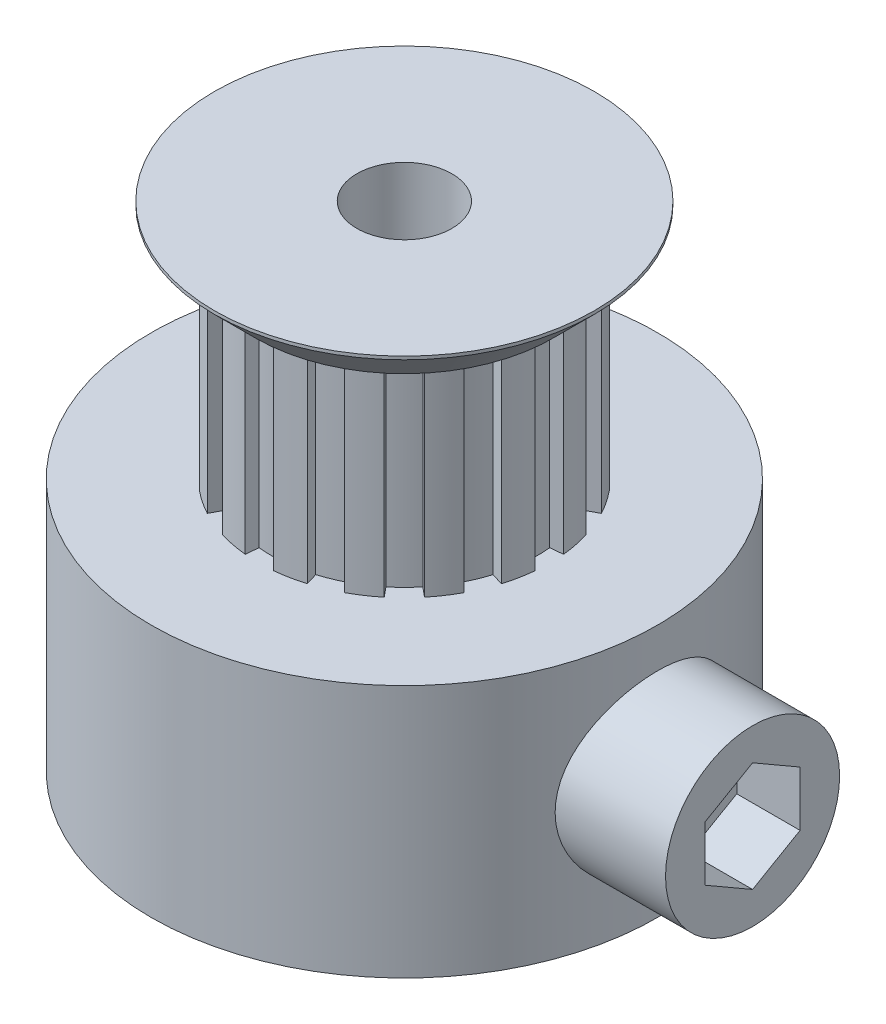
SolidWorks part; units mm, degrees
ref_plane "Front Plane" through (0, 0, 0) normal (0, 0, 1) x (1, 0, 0)
ref_plane "Top Plane" through (0, 0, 0) normal (0, 1, 0) x (1, 0, 0)
ref_plane "Right Plane" through (0, 0, 0) normal (1, 0, 0) x (0, 0, -1)
sketch "Sketch1" plane through (0, 0, 0) normal (0, 1, 0) x (1, 0, 0)
  circle A0 centre (0, 0) radius 8
  dimension "D1" = 16
extrude "Boss-Extrude1" add sketch "Sketch1" along normal blind 8
sketch "Sketch2" plane through (0, 8, 0) normal (0, 1, 0) x (1, 0, 0)
  circle A0 centre (0, 0) radius 4.6
  dimension "D1" = 9.2
extrude "Boss-Extrude2" add sketch "Sketch2" along normal blind 6.2
sketch "Sketch6" plane through (0, 14.2, 0) normal (0, 1, 0) x (1, 0, 0)
  line L0 (0, 0) -> (0, 4.6) construction
  line L1 (-0.4509, 4.5778) -> (0, 0) construction
  line L2 (0.4509, 4.5778) -> (0, 0) construction
  line L3 (-0.4509, 4.5778) -> (-0.4117, 4.1798)
  line L4 (0.4509, 4.5778) -> (0.4117, 4.1798)
  line L5 (2.1684, 4.0568) -> (1.9799, 3.7041)
  line L6 (1.3353, 4.4019) -> (1.2192, 4.0191)
  line L7 (3.5558, 2.9182) -> (3.2466, 2.6645)
  line L8 (2.9182, 3.5558) -> (2.6645, 3.2466)
  line L9 (4.4019, 1.3353) -> (4.0191, 1.2192)
  line L10 (4.0568, 2.1684) -> (3.7041, 1.9799)
  line L11 (4.5778, -0.4509) -> (4.1798, -0.4117)
  line L12 (4.5778, 0.4509) -> (4.1798, 0.4117)
  line L13 (4.0568, -2.1684) -> (3.7041, -1.9799)
  line L14 (4.4019, -1.3353) -> (4.0191, -1.2192)
  line L15 (2.9182, -3.5558) -> (2.6645, -3.2466)
  line L16 (3.5558, -2.9182) -> (3.2466, -2.6645)
  line L17 (1.3353, -4.4019) -> (1.2192, -4.0191)
  line L18 (2.1684, -4.0568) -> (1.9799, -3.7041)
  line L19 (-0.4509, -4.5778) -> (-0.4117, -4.1798)
  line L20 (0.4509, -4.5778) -> (0.4117, -4.1798)
  line L21 (-2.1684, -4.0568) -> (-1.9799, -3.7041)
  line L22 (-1.3353, -4.4019) -> (-1.2192, -4.0191)
  line L23 (-3.5558, -2.9182) -> (-3.2466, -2.6645)
  line L24 (-2.9182, -3.5558) -> (-2.6645, -3.2466)
  line L25 (-4.4019, -1.3353) -> (-4.0191, -1.2192)
  line L26 (-4.0568, -2.1684) -> (-3.7041, -1.9799)
  line L27 (-4.5778, 0.4509) -> (-4.1798, 0.4117)
  line L28 (-4.5778, -0.4509) -> (-4.1798, -0.4117)
  line L29 (-4.0568, 2.1684) -> (-3.7041, 1.9799)
  line L30 (-4.4019, 1.3353) -> (-4.0191, 1.2192)
  line L31 (-2.9182, 3.5558) -> (-2.6645, 3.2466)
  line L32 (-3.5558, 2.9182) -> (-3.2466, 2.6645)
  line L33 (-1.3353, 4.4019) -> (-1.2192, 4.0191)
  line L34 (-2.1684, 4.0568) -> (-1.9799, 3.7041)
  circle A0 centre (0, 0) radius 4.6 construction
  circle A1 centre (0, 0) radius 4.6 construction
  arc A2 (-0.4509, 4.5778) -> (0.4509, 4.5778) centre (0, 0) cw
  circle A3 centre (0, 0) radius 4.6 construction
  arc A4 (-0.4117, 4.1798) -> (0.4117, 4.1798) centre (0, 0) cw
  arc A5 (1.2192, 4.0191) -> (1.9799, 3.7041) centre (0, 0) cw
  arc A6 (1.3353, 4.4019) -> (2.1684, 4.0568) centre (0, 0) cw
  arc A7 (2.6645, 3.2466) -> (3.2466, 2.6645) centre (0, 0) cw
  arc A8 (2.9182, 3.5558) -> (3.5558, 2.9182) centre (0, 0) cw
  arc A9 (3.7041, 1.9799) -> (4.0191, 1.2192) centre (0, 0) cw
  arc A10 (4.0568, 2.1684) -> (4.4019, 1.3353) centre (0, 0) cw
  arc A11 (4.1798, 0.4117) -> (4.1798, -0.4117) centre (0, 0) cw
  arc A12 (4.5778, 0.4509) -> (4.5778, -0.4509) centre (0, 0) cw
  arc A13 (4.0191, -1.2192) -> (3.7041, -1.9799) centre (0, 0) cw
  arc A14 (4.4019, -1.3353) -> (4.0568, -2.1684) centre (0, 0) cw
  arc A15 (3.2466, -2.6645) -> (2.6645, -3.2466) centre (0, 0) cw
  arc A16 (3.5558, -2.9182) -> (2.9182, -3.5558) centre (0, 0) cw
  arc A17 (1.9799, -3.7041) -> (1.2192, -4.0191) centre (0, 0) cw
  arc A18 (2.1684, -4.0568) -> (1.3353, -4.4019) centre (0, 0) cw
  arc A19 (0.4117, -4.1798) -> (-0.4117, -4.1798) centre (0, 0) cw
  arc A20 (0.4509, -4.5778) -> (-0.4509, -4.5778) centre (0, 0) cw
  arc A21 (-1.2192, -4.0191) -> (-1.9799, -3.7041) centre (0, 0) cw
  arc A22 (-1.3353, -4.4019) -> (-2.1684, -4.0568) centre (0, 0) cw
  arc A23 (-2.6645, -3.2466) -> (-3.2466, -2.6645) centre (0, 0) cw
  arc A24 (-2.9182, -3.5558) -> (-3.5558, -2.9182) centre (0, 0) cw
  arc A25 (-3.7041, -1.9799) -> (-4.0191, -1.2192) centre (0, 0) cw
  arc A26 (-4.0568, -2.1684) -> (-4.4019, -1.3353) centre (0, 0) cw
  arc A27 (-4.1798, -0.4117) -> (-4.1798, 0.4117) centre (0, 0) cw
  arc A28 (-4.5778, -0.4509) -> (-4.5778, 0.4509) centre (0, 0) cw
  arc A29 (-4.0191, 1.2192) -> (-3.7041, 1.9799) centre (0, 0) cw
  arc A30 (-4.4019, 1.3353) -> (-4.0568, 2.1684) centre (0, 0) cw
  arc A31 (-3.2466, 2.6645) -> (-2.6645, 3.2466) centre (0, 0) cw
  arc A32 (-3.5558, 2.9182) -> (-2.9182, 3.5558) centre (0, 0) cw
  arc A33 (-1.9799, 3.7041) -> (-1.2192, 4.0191) centre (0, 0) cw
  arc A34 (-2.1684, 4.0568) -> (-1.3353, 4.4019) centre (0, 0) cw
  point P11 (0, 4.2)
  point P73 (0, 0)
  dimension "D1" = 0.4
  dimension "D2" = 11.25
  dimension "D3" = 16
extrude "Cut-Extrude2" cut sketch "Sketch6" against normal up to surface (6.2 mm away) up to face at (0, 8, 4.6)
sketch "Sketch3" plane through (0, 14.2, 0) normal (0, 1, 0) x (1, 0, 0)
  circle A0 centre (0, 0) radius 6
  dimension "D1" = 12
extrude "Boss-Extrude3" add sketch "Sketch3" along normal blind 1.4
chamfer "Chamfer1" distance 1.3 angle 45 1 edges at (0, 14.2, 6)
sketch "Sketch4" plane through (0, 0, 0) normal (1, 0, 0) x (0, 0, -1)
  line L0 (0, 8) -> (0, 0) construction
  line L1 (8, 8) -> (-8, 8) construction
  circle A0 centre (0, 4) radius 2.75
  point P2 (0, 0)
  point P8 (0, 4)
  point P9 (0, 0)
  dimension "D1" = 5.5
extrude "Boss-Extrude4" add sketch "Sketch4" along normal blind 11
sketch "Sketch5" plane through (11, 0, 0) normal (1, 0, 0) x (0, 0, -1)
  line L1 (0, 2.2679) -> (1.5, 3.134)
  line L2 (1.5, 3.134) -> (1.5, 4.866)
  line L3 (1.5, 4.866) -> (0, 5.7321)
  line L4 (0, 5.7321) -> (-1.5, 4.866)
  line L5 (-1.5, 4.866) -> (-1.5, 3.134)
  line L6 (-1.5, 3.134) -> (0, 2.2679)
  circle A0 centre (0, 4) radius 1.5 construction
  dimension "D1" = 3
extrude "Cut-Extrude1" cut sketch "Sketch5" against normal blind 2
sketch "Sketch7" plane through (0, 0, 0) normal (0, -1, 0) x (1, 0, 0)
  circle A0 centre (0, 0) radius 1.5
  dimension "D1" = 3
extrude "Cut-Extrude3" cut sketch "Sketch7" against normal through all
